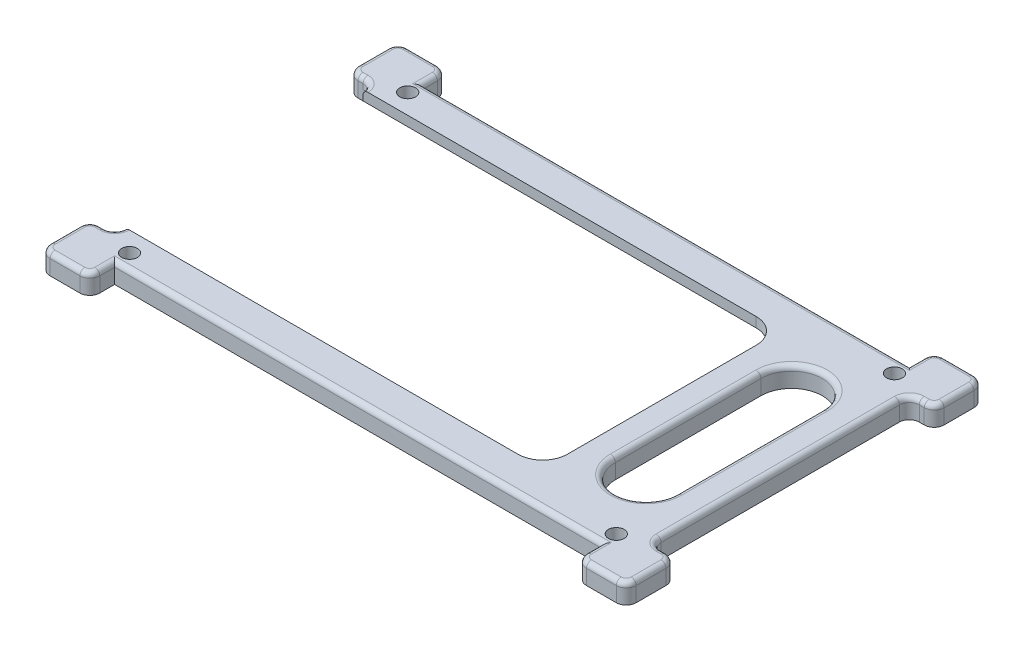
SolidWorks part; units mm, degrees
ref_plane "Alzado" through (0, 0, 0) normal (0, 0, 1) x (1, 0, 0)
ref_plane "Planta" through (0, 0, 0) normal (0, 1, 0) x (1, 0, 0)
ref_plane "Vista lateral" through (0, 0, 0) normal (1, 0, 0) x (0, 0, -1)
sketch "Croquis1" plane through (0, 0, 0) normal (0, 1, 0) x (1, 0, 0)
  line L0 (44.6032, 4.4321) -> (-63.3968, 4.4321) construction
  line L1 (-63.3968, 4.4321) -> (-9.3968, 4.4321) construction
  line L2 (-9.3968, 4.4321) -> (-9.3968, -19.5679) construction
  line L56 (-64.3968, -29.0679) -> (-64.3968, -26.5679)
  line L57 (-64.3968, -26.5679) -> (45.6032, -26.5679)
  line L58 (45.6032, -26.5679) -> (45.6032, -29.0679)
  line L59 (45.6032, -29.0679) -> (39.6032, -29.0679)
  line L60 (39.6032, -29.0679) -> (39.6032, -29.5679)
  line L61 (41.6032, -31.5679) -> (47.6032, -31.5679)
  line L62 (49.6032, -29.5679) -> (49.6032, -23.5679)
  line L63 (47.6032, -21.5679) -> (46.6032, -21.5679)
  line L64 (44.6032, -19.5679) -> (44.6032, 28.4321)
  line L65 (46.6032, 30.4321) -> (47.6032, 30.4321)
  line L66 (49.6032, 32.4321) -> (49.6032, 38.4321)
  line L67 (47.6032, 40.4321) -> (41.6032, 40.4321)
  line L68 (39.6032, 38.4321) -> (39.6032, 37.9321)
  line L69 (39.6032, 37.9321) -> (45.6032, 37.9321)
  line L70 (45.6032, 37.9321) -> (45.6032, 35.4321)
  line L71 (45.6032, 35.4321) -> (-64.3968, 35.4321)
  line L72 (-64.3968, 35.4321) -> (-64.3968, 37.9321)
  line L73 (-64.3968, 37.9321) -> (-58.3968, 37.9321)
  line L74 (-58.3968, 37.9321) -> (-58.3968, 38.4321)
  line L75 (-60.3968, 40.4321) -> (-66.3968, 40.4321)
  line L76 (-68.3968, 38.4321) -> (-68.3968, 32.4321)
  line L77 (-66.3968, 30.4321) -> (-65.3968, 30.4321)
  line L78 (-63.3968, 28.4321) -> (-63.3968, -19.5679)
  line L79 (-65.3968, -21.5679) -> (-66.3968, -21.5679)
  line L80 (-68.3968, -23.5679) -> (-68.3968, -29.5679)
  line L81 (-66.3968, -31.5679) -> (-60.3968, -31.5679)
  line L82 (-58.3968, -29.5679) -> (-58.3968, -29.0679)
  line L83 (-58.3968, -29.0679) -> (-64.3968, -29.0679)
  circle A0 centre (32.2506, -10.2197) radius 6.9506
  circle A1 centre (32.2506, 19.0839) radius 5.7677
  circle A2 centre (39.6032, -23.5679) radius 1.5875
  circle A3 centre (-58.3968, -23.5679) radius 1.5875
  circle A4 centre (39.6032, 32.4321) radius 1.5875
  circle A5 centre (-58.3968, 32.4321) radius 1.5875
  arc A32 (39.6032, -29.5679) -> (41.6032, -31.5679) centre (41.6032, -29.5679) ccw
  arc A33 (47.6032, -31.5679) -> (49.6032, -29.5679) centre (47.6032, -29.5679) ccw
  arc A34 (49.6032, -23.5679) -> (47.6032, -21.5679) centre (47.6032, -23.5679) ccw
  arc A35 (44.6032, -19.5679) -> (46.6032, -21.5679) centre (46.6032, -19.5679) ccw
  arc A36 (46.6032, 30.4321) -> (44.6032, 28.4321) centre (46.6032, 28.4321) ccw
  arc A37 (47.6032, 30.4321) -> (49.6032, 32.4321) centre (47.6032, 32.4321) ccw
  arc A38 (49.6032, 38.4321) -> (47.6032, 40.4321) centre (47.6032, 38.4321) ccw
  arc A39 (41.6032, 40.4321) -> (39.6032, 38.4321) centre (41.6032, 38.4321) ccw
  arc A40 (-58.3968, 38.4321) -> (-60.3968, 40.4321) centre (-60.3968, 38.4321) ccw
  arc A41 (-66.3968, 40.4321) -> (-68.3968, 38.4321) centre (-66.3968, 38.4321) ccw
  arc A42 (-68.3968, 32.4321) -> (-66.3968, 30.4321) centre (-66.3968, 32.4321) ccw
  arc A43 (-63.3968, 28.4321) -> (-65.3968, 30.4321) centre (-65.3968, 28.4321) ccw
  arc A44 (-65.3968, -21.5679) -> (-63.3968, -19.5679) centre (-65.3968, -19.5679) ccw
  arc A45 (-66.3968, -21.5679) -> (-68.3968, -23.5679) centre (-66.3968, -23.5679) ccw
  arc A46 (-68.3968, -29.5679) -> (-66.3968, -31.5679) centre (-66.3968, -29.5679) ccw
  arc A47 (-60.3968, -31.5679) -> (-58.3968, -29.5679) centre (-60.3968, -29.5679) ccw
sketch "Croquis2" plane through (0, 0, 0) normal (0, 1, 0) x (1, 0, 0)
  line L0 (44.6032, 28.4321) -> (44.6032, -19.5679)
  line L1 (32.2506, 19.0839) -> (32.2506, -10.2197) construction
  line L2 (38.4343, 19.0839) -> (38.4343, -10.2197)
  line L3 (-66.3968, 30.4321) -> (-65.3968, 30.4321) construction
  line L4 (-68.3968, 38.4321) -> (-68.3968, 32.4321) construction
  line L5 (-60.3968, 40.4321) -> (-66.3968, 40.4321) construction
  line L6 (-58.3968, 37.9321) -> (-58.3968, 38.4321) construction
  line L7 (-58.3968, 37.9321) -> (-58.3968, 38.4321)
  line L8 (-60.3968, 40.4321) -> (-66.3968, 40.4321)
  line L9 (-68.3968, 38.4321) -> (-68.3968, 32.4321)
  line L10 (-66.3968, 30.4321) -> (-65.3968, 30.4321)
  line L11 (-58.3968, 37.9321) -> (-58.3968, 35.4321)
  line L12 (45.6032, 35.4321) -> (-64.3968, 35.4321) construction
  line L13 (-63.3968, 4.4321) -> (-37.3235, 4.4321) construction
  line L14 (44.6032, 4.4321) -> (-63.3968, 4.4321) construction
  line L15 (-58.3968, -29.0679) -> (-58.3968, -26.5679)
  line L16 (-66.3968, -21.5679) -> (-65.3968, -21.5679)
  line L17 (-68.3968, -29.5679) -> (-68.3968, -23.5679)
  line L18 (-60.3968, -31.5679) -> (-66.3968, -31.5679)
  line L19 (-58.3968, -29.0679) -> (-58.3968, -29.5679)
  line L20 (-9.3968, 4.4321) -> (-9.3968, 17.9126) construction
  line L21 (-58.3968, 37.9321) -> (-58.3968, 38.4321)
  line L22 (-60.3968, 40.4321) -> (-66.3968, 40.4321)
  line L23 (-68.3968, 38.4321) -> (-68.3968, 32.4321)
  line L24 (-66.3968, 30.4321) -> (-65.3968, 30.4321)
  line L25 (-58.3968, 37.9321) -> (-58.3968, 35.4321)
  line L26 (-58.3968, -29.0679) -> (-58.3968, -26.5679)
  line L27 (-66.3968, -21.5679) -> (-65.3968, -21.5679)
  line L28 (-68.3968, -29.5679) -> (-68.3968, -23.5679)
  line L29 (-60.3968, -31.5679) -> (-66.3968, -31.5679)
  line L30 (-58.3968, -29.0679) -> (-58.3968, -29.5679)
  line L31 (44.6032, 4.4321) -> (18.5298, 4.4321) construction
  line L32 (39.6032, -29.0679) -> (39.6032, -29.5679)
  line L33 (41.6032, -31.5679) -> (47.6032, -31.5679)
  line L34 (49.6032, -29.5679) -> (49.6032, -23.5679)
  line L35 (47.6032, -21.5679) -> (46.6032, -21.5679)
  line L36 (39.6032, -29.0679) -> (39.6032, -26.5679)
  line L37 (39.6032, 37.9321) -> (39.6032, 35.4321)
  line L38 (47.6032, 30.4321) -> (46.6032, 30.4321)
  line L39 (49.6032, 38.4321) -> (49.6032, 32.4321)
  line L40 (41.6032, 40.4321) -> (47.6032, 40.4321)
  line L41 (39.6032, 37.9321) -> (39.6032, 38.4321)
  line L42 (39.6032, -29.0679) -> (39.6032, -29.5679)
  line L43 (41.6032, -31.5679) -> (47.6032, -31.5679)
  line L44 (49.6032, -29.5679) -> (49.6032, -23.5679)
  line L45 (47.6032, -21.5679) -> (46.6032, -21.5679)
  line L46 (39.6032, -29.0679) -> (39.6032, -26.5679)
  line L47 (39.6032, 37.9321) -> (39.6032, 35.4321)
  line L48 (47.6032, 30.4321) -> (46.6032, 30.4321)
  line L49 (49.6032, 38.4321) -> (49.6032, 32.4321)
  line L50 (41.6032, 40.4321) -> (47.6032, 40.4321)
  line L51 (39.6032, 37.9321) -> (39.6032, 38.4321)
  line L52 (26.0669, 19.0839) -> (26.0669, -10.2197)
  line L53 (-58.3968, 35.4321) -> (39.6032, 35.4321)
  line L54 (-58.3968, -26.5679) -> (39.6032, -26.5679)
  line L55 (-63.3968, 28.4321) -> (15.777, 28.4321)
  line L56 (20.777, 23.4321) -> (20.777, -14.5679)
  line L57 (15.777, -19.5679) -> (-63.3968, -19.5679)
  arc A1 (-68.3968, 32.4321) -> (-66.3968, 30.4321) centre (-66.3968, 32.4321) ccw construction
  arc A2 (-66.3968, 40.4321) -> (-68.3968, 38.4321) centre (-66.3968, 38.4321) ccw construction
  arc A3 (-58.3968, 38.4321) -> (-60.3968, 40.4321) centre (-60.3968, 38.4321) ccw construction
  circle A4 centre (-58.3968, 32.4321) radius 1.5875 construction
  circle A5 centre (-58.3968, 32.4321) radius 1.5875
  arc A6 (-58.3968, 38.4321) -> (-60.3968, 40.4321) centre (-60.3968, 38.4321) ccw
  arc A7 (-66.3968, 40.4321) -> (-68.3968, 38.4321) centre (-66.3968, 38.4321) ccw
  arc A8 (-68.3968, 32.4321) -> (-66.3968, 30.4321) centre (-66.3968, 32.4321) ccw
  arc A9 (-63.3968, 28.4321) -> (-65.3968, 30.4321) centre (-65.3968, 28.4321) ccw construction
  arc A10 (-63.3968, 28.4321) -> (-65.3968, 30.4321) centre (-65.3968, 28.4321) ccw
  arc A11 (-63.3968, -19.5679) -> (-65.3968, -21.5679) centre (-65.3968, -19.5679) cw
  arc A12 (-68.3968, -23.5679) -> (-66.3968, -21.5679) centre (-66.3968, -23.5679) cw
  arc A13 (-66.3968, -31.5679) -> (-68.3968, -29.5679) centre (-66.3968, -29.5679) cw
  arc A14 (-58.3968, -29.5679) -> (-60.3968, -31.5679) centre (-60.3968, -29.5679) cw
  circle A15 centre (-58.3968, -23.5679) radius 1.5875
  circle A16 centre (-58.3968, 32.4321) radius 1.5875
  arc A17 (-58.3968, 38.4321) -> (-60.3968, 40.4321) centre (-60.3968, 38.4321) ccw
  arc A18 (-66.3968, 40.4321) -> (-68.3968, 38.4321) centre (-66.3968, 38.4321) ccw
  arc A19 (-68.3968, 32.4321) -> (-66.3968, 30.4321) centre (-66.3968, 32.4321) ccw
  arc A20 (-63.3968, 28.4321) -> (-65.3968, 30.4321) centre (-65.3968, 28.4321) ccw
  arc A21 (-63.3968, -19.5679) -> (-65.3968, -21.5679) centre (-65.3968, -19.5679) cw
  arc A22 (-68.3968, -23.5679) -> (-66.3968, -21.5679) centre (-66.3968, -23.5679) cw
  arc A23 (-66.3968, -31.5679) -> (-68.3968, -29.5679) centre (-66.3968, -29.5679) cw
  arc A24 (-58.3968, -29.5679) -> (-60.3968, -31.5679) centre (-60.3968, -29.5679) cw
  circle A25 centre (-58.3968, -23.5679) radius 1.5875
  circle A26 centre (39.6032, -23.5679) radius 1.5875
  arc A27 (39.6032, -29.5679) -> (41.6032, -31.5679) centre (41.6032, -29.5679) ccw
  arc A28 (47.6032, -31.5679) -> (49.6032, -29.5679) centre (47.6032, -29.5679) ccw
  arc A29 (49.6032, -23.5679) -> (47.6032, -21.5679) centre (47.6032, -23.5679) ccw
  arc A30 (44.6032, -19.5679) -> (46.6032, -21.5679) centre (46.6032, -19.5679) ccw
  arc A31 (44.6032, 28.4321) -> (46.6032, 30.4321) centre (46.6032, 28.4321) cw
  arc A32 (49.6032, 32.4321) -> (47.6032, 30.4321) centre (47.6032, 32.4321) cw
  arc A33 (47.6032, 40.4321) -> (49.6032, 38.4321) centre (47.6032, 38.4321) cw
  arc A34 (39.6032, 38.4321) -> (41.6032, 40.4321) centre (41.6032, 38.4321) cw
  circle A35 centre (39.6032, 32.4321) radius 1.5875
  circle A36 centre (39.6032, -23.5679) radius 1.5875
  arc A37 (39.6032, -29.5679) -> (41.6032, -31.5679) centre (41.6032, -29.5679) ccw
  arc A38 (47.6032, -31.5679) -> (49.6032, -29.5679) centre (47.6032, -29.5679) ccw
  arc A39 (49.6032, -23.5679) -> (47.6032, -21.5679) centre (47.6032, -23.5679) ccw
  arc A40 (44.6032, -19.5679) -> (46.6032, -21.5679) centre (46.6032, -19.5679) ccw
  arc A41 (44.6032, 28.4321) -> (46.6032, 30.4321) centre (46.6032, 28.4321) cw
  arc A42 (49.6032, 32.4321) -> (47.6032, 30.4321) centre (47.6032, 32.4321) cw
  arc A43 (47.6032, 40.4321) -> (49.6032, 38.4321) centre (47.6032, 38.4321) cw
  arc A44 (39.6032, 38.4321) -> (41.6032, 40.4321) centre (41.6032, 38.4321) cw
  circle A45 centre (39.6032, 32.4321) radius 1.5875
  arc A46 (38.4343, 19.0839) -> (26.0669, 19.0839) centre (32.2506, 19.0839) ccw
  arc A47 (26.0669, -10.2197) -> (38.4343, -10.2197) centre (32.2506, -10.2197) ccw
  arc A48 (20.777, 23.4321) -> (15.777, 28.4321) centre (15.777, 23.4321) ccw
  arc A49 (20.777, -14.5679) -> (15.777, -19.5679) centre (15.777, -14.5679) cw
  point P85 (32.2506, 4.4321)
  dimension "D1" = 5
extrude "Saliente-Extruir1" add sketch "Croquis2" along normal blind 4 contours A34 L41 L37 L53 L11 L7 A6 L8 A7 L9 A8 L10 A10 L55 L56 L57 A11 L16 A12 L17 A13 L18 A14 L19 L15 L54 L36 L32 A27 L33 A28 L34 A29 L35 A30 L0 A31 L38 A32 L39 A33 L40 A47 L52 A46 L2 A15 A5
sketch "Croquis3" plane through (-68.3968, 0, 0) normal (-1, 0, 0) x (0, 0, 1)
  line L0 (21.5679, 4) -> (21.5679, 0) construction
  line L1 (21.5679, 2) -> (15.1279, 2)
  line L2 (21.5679, 2) -> (21.5679, -0.682)
  line L3 (21.5679, -0.682) -> (15.1279, -0.682)
  line L4 (15.1279, 2) -> (15.1279, -0.682)
  line L5 (-4.4321, 4) -> (-4.4321, 12.4698) construction
  line L6 (-23.4321, 4) -> (14.5679, 4) construction
  line L7 (-23.9921, 2) -> (-23.9921, -0.682)
  line L8 (-30.4321, -0.682) -> (-23.9921, -0.682)
  line L9 (-30.4321, 2) -> (-30.4321, -0.682)
  line L10 (-30.4321, 2) -> (-23.9921, 2)
  line L12 (-23.9921, 2) -> (15.1279, 2)
  line L13 (-23.9921, 2) -> (-23.9921, -0.682)
  line L14 (-23.9921, -0.682) -> (15.1279, -0.682)
  line L15 (15.1279, 2) -> (15.1279, -0.682)
extrude "Cortar-Extruir1" cut sketch "Croquis3" against normal blind 92 contours L10 L9 L8 L7 | L7 L14 L4 L12 | L1 L4 L3 L2
fillet "Redondeo1" radius 1 39 edges at (32.2506, 4, -25.2676) (26.0669, 4, -4.4321) (32.2506, 4, 16.4033) (-58.3968, 4, -36.9321) (-58.9826, 4, -39.8463) (-63.3968, 4, -40.4321) (-67.8111, 4, -39.8463) (-68.3968, 4, -35.4321) (-67.8111, 4, -31.0179) (-65.8968, 4, -30.4321) (-63.9826, 4, 20.9821) (-65.8968, 4, 21.5679) (-67.8111, 4, 22.1537) (-68.3968, 4, 26.5679) (-67.8111, 4, 30.9821) (-63.3968, 4, 31.5679) (-58.9826, 4, 30.9821) (39.6032, 4, 28.0679) (40.1889, 4, 30.9821) (44.6032, 4, 31.5679) (49.0174, 4, 30.9821) (49.6032, 4, 26.5679) (49.0174, 4, 22.1537) (47.1032, 4, 21.5679) (45.1889, 4, 20.9821) (44.6032, 4, -4.4321) (45.1889, 4, -29.8463) (47.1032, 4, -30.4321) (49.0174, 4, -31.0179) (49.6032, 4, -35.4321) (49.0174, 4, -39.8463) (44.6032, 4, -40.4321) (40.1889, 4, -39.8463) (38.4343, 4, -4.4321) (-63.9826, 4, -29.8463) (-58.3968, 4, 28.0679) (-9.3968, 4, 26.5679) (39.6032, 4, -36.9321) (-9.3968, 4, -35.4321)
